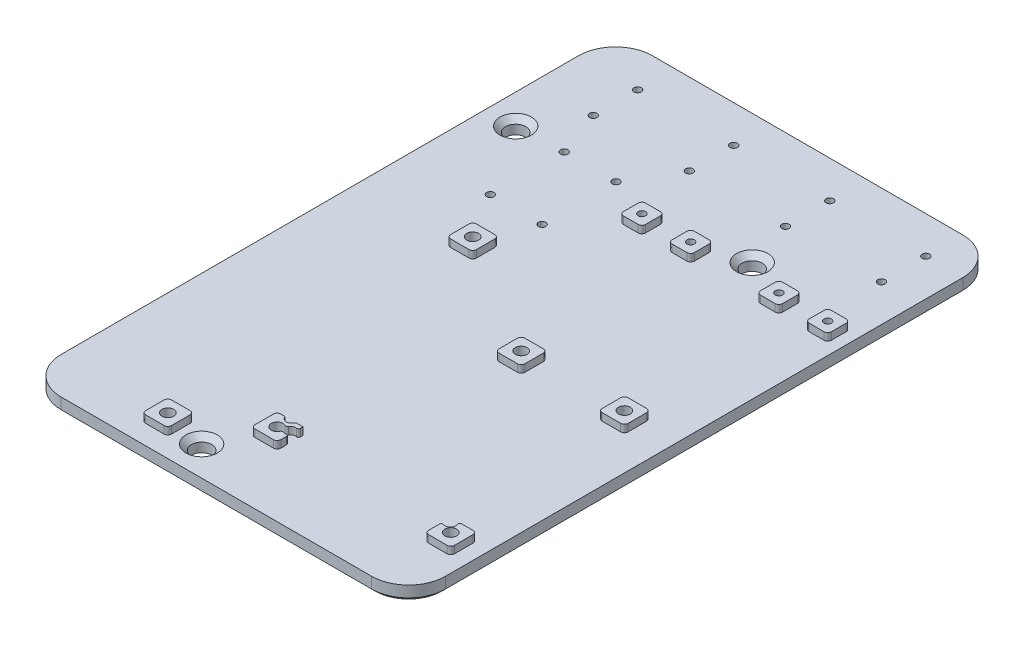
SolidWorks part; units mm, degrees
ref_plane "Front Plane" through (0, 0, 0) normal (0, 0, 1) x (1, 0, 0)
ref_plane "Top Plane" through (0, 0, 0) normal (0, 1, 0) x (1, 0, 0)
ref_plane "Right Plane" through (0, 0, 0) normal (1, 0, 0) x (0, 0, -1)
sketch "Sketch1" plane through (0, 0, 0) normal (0, 1, 0) x (1, 0, 0)
  line L1 (5, -5) -> (-99, -5)
  line L2 (5, -5) -> (5, 155)
  line L3 (5, 155) -> (-99, 155)
  line L4 (-99, -5) -> (-99, 155)
  circle A0 centre (-1.09, 114.53) radius 1
  circle A1 centre (-14.29, 114.53) radius 1
  circle A3 centre (-38.19, 114.53) radius 1
  circle A4 centre (-51.39, 114.53) radius 1
  circle A5 centre (-68.89, 86.25) radius 1.6
  circle A6 centre (-68.89, 3.75) radius 1.6
  circle A7 centre (-50.8, 15.24) radius 1.6
  circle A8 centre (-2.54, 13.97) radius 1.6
  circle A9 centre (-7.62, 66.04) radius 1.6
  circle A10 centre (-35.56, 66.04) radius 1.6
  point P35 (5, -2.4567)
  dimension "D3" = 2
  dimension "D4" = 160
  dimension "D5" = 3.2
  dimension "D1" = 104
  dimension "D2" = 5
  dimension "D6" = 5
extrude "Boss-Extrude1" add sketch "Sketch1" against normal blind 4
sketch "Sketch2" plane through (0, 0, 0) normal (0, -1, 0) x (-1, 0, 0)
  line L1 (65.39, 7.25) -> (72.39, 7.25)
  line L2 (65.39, 7.25) -> (65.39, 0.25)
  line L3 (65.39, 0.25) -> (72.39, 0.25)
  line L4 (72.39, 7.25) -> (72.39, 0.25)
  line L5 (65.39, 7.25) -> (72.39, 0.25) construction
  line L6 (65.39, 0.25) -> (72.39, 7.25) construction
  line L7 (65.39, 89.75) -> (72.39, 89.75)
  line L8 (65.39, 89.75) -> (65.39, 82.75)
  line L9 (65.39, 82.75) -> (72.39, 82.75)
  line L10 (72.39, 89.75) -> (72.39, 82.75)
  line L11 (65.39, 89.75) -> (72.39, 82.75) construction
  line L12 (65.39, 82.75) -> (72.39, 89.75) construction
  line L13 (48.39, 117.53) -> (54.39, 117.53)
  line L14 (48.39, 117.53) -> (48.39, 111.53)
  line L15 (48.39, 111.53) -> (54.39, 111.53)
  line L16 (54.39, 117.53) -> (54.39, 111.53)
  line L17 (48.39, 117.53) -> (54.39, 111.53) construction
  line L18 (48.39, 111.53) -> (54.39, 117.53) construction
  line L19 (41.19, 117.53) -> (35.19, 117.53)
  line L20 (41.19, 117.53) -> (41.19, 111.53)
  line L21 (41.19, 111.53) -> (35.19, 111.53)
  line L22 (35.19, 117.53) -> (35.19, 111.53)
  line L23 (41.19, 117.53) -> (35.19, 111.53) construction
  line L24 (41.19, 111.53) -> (35.19, 117.53) construction
  line L25 (11.29, 117.53) -> (17.29, 117.53)
  line L26 (11.29, 117.53) -> (11.29, 111.53)
  line L27 (11.29, 111.53) -> (17.29, 111.53)
  line L28 (17.29, 117.53) -> (17.29, 111.53)
  line L29 (11.29, 117.53) -> (17.29, 111.53) construction
  line L30 (11.29, 111.53) -> (17.29, 117.53) construction
  line L31 (4.09, 117.53) -> (-1.91, 117.53)
  line L32 (4.09, 117.53) -> (4.09, 111.53)
  line L33 (4.09, 111.53) -> (-1.91, 111.53)
  line L34 (-1.91, 117.53) -> (-1.91, 111.53)
  line L35 (4.09, 117.53) -> (-1.91, 111.53) construction
  line L36 (4.09, 111.53) -> (-1.91, 117.53) construction
  line L37 (-0.96, 17.47) -> (6.04, 17.47)
  line L38 (-0.96, 17.47) -> (-0.96, 10.47)
  line L39 (-0.96, 10.47) -> (6.04, 10.47)
  line L40 (6.04, 17.47) -> (6.04, 10.47)
  line L41 (-0.96, 17.47) -> (6.04, 10.47) construction
  line L42 (-0.96, 10.47) -> (6.04, 17.47) construction
  line L43 (54.3, 18.74) -> (47.3, 18.74)
  line L44 (54.3, 18.74) -> (54.3, 11.74)
  line L45 (54.3, 11.74) -> (47.3, 11.74)
  line L46 (47.3, 18.74) -> (47.3, 11.74)
  line L47 (54.3, 18.74) -> (47.3, 11.74) construction
  line L48 (54.3, 11.74) -> (47.3, 18.74) construction
  line L49 (32.06, 69.54) -> (39.06, 69.54)
  line L50 (32.06, 69.54) -> (32.06, 62.54)
  line L51 (32.06, 62.54) -> (39.06, 62.54)
  line L52 (39.06, 69.54) -> (39.06, 62.54)
  line L53 (32.06, 69.54) -> (39.06, 62.54) construction
  line L54 (32.06, 62.54) -> (39.06, 69.54) construction
  line L55 (4.12, 69.54) -> (11.12, 69.54)
  line L56 (4.12, 69.54) -> (4.12, 62.54)
  line L57 (4.12, 62.54) -> (11.12, 62.54)
  line L58 (11.12, 69.54) -> (11.12, 62.54)
  line L59 (4.12, 69.54) -> (11.12, 62.54) construction
  line L60 (4.12, 62.54) -> (11.12, 69.54) construction
  circle A1 centre (35.56, 66.04) radius 1.6
  circle A2 centre (35.56, 66.04) radius 1.6
  circle A3 centre (68.89, 86.25) radius 1.6
  circle A4 centre (68.89, 86.25) radius 1.6
  circle A5 centre (51.39, 114.53) radius 1
  circle A6 centre (51.39, 114.53) radius 1
  circle A7 centre (38.19, 114.53) radius 1
  circle A8 centre (38.19, 114.53) radius 1
  circle A9 centre (14.29, 114.53) radius 1
  circle A10 centre (14.29, 114.53) radius 1
  circle A11 centre (1.09, 114.53) radius 1
  circle A12 centre (1.09, 114.53) radius 1
  circle A13 centre (7.62, 66.04) radius 1.6
  circle A14 centre (7.62, 66.04) radius 1.6
  circle A15 centre (2.54, 13.97) radius 1.6
  circle A16 centre (2.54, 13.97) radius 1.6
  circle A17 centre (50.8, 15.24) radius 1.6
  circle A18 centre (50.8, 15.24) radius 1.6
  circle A19 centre (68.89, 3.75) radius 1.6
  circle A20 centre (68.89, 3.75) radius 1.6
  point P0 (68.89, 3.75)
  point P6 (68.89, 86.25)
  point P12 (51.39, 114.53)
  point P18 (38.19, 114.53)
  point P24 (14.29, 114.53)
  point P30 (1.09, 114.53)
  point P36 (2.54, 13.97)
  point P42 (50.8, 15.24)
  point P48 (35.56, 66.04)
  point P54 (7.62, 66.04)
  dimension "D1" = 6
  dimension "D2" = 7
  dimension "D3" = 0
  dimension "D4" = 0
  dimension "D5" = 0
  dimension "D6" = 0
  dimension "D7" = 0
  dimension "D8" = 0
  dimension "D9" = 0
  dimension "D10" = 0
  dimension "D11" = 0
  dimension "D12" = 0
extrude "Boss-Extrude2" add sketch "Sketch2" against normal blind 2
sketch "Sketch3" plane through (0, 2, 0) normal (0, 1, 0) x (1, 0, 0)
  line L0 (-47.3, 18.74) -> (-47.3, 11.74) construction
  line L1 (-54.3, 18.74) -> (-47.3, 18.74) construction
  line L2 (-4.8463, 16.1519) -> (-6.8463, 18.1519) construction
  line L3 (-5.8363, 15.162) -> (-7.8363, 17.162)
  line L4 (-3.8564, 17.1419) -> (-5.8564, 19.1419)
  line L5 (-6.04, 17.47) -> (0.96, 17.47) construction
  circle A0 centre (-50.7183, 19.0424) radius 1.4
  circle A1 centre (-48.1702, 16.1519) radius 1.4
  circle A2 centre (-4.8463, 16.1519) radius 1.4 construction
  arc A3 (-5.8363, 15.162) -> (-3.8564, 17.1419) centre (-4.8463, 16.1519) ccw
  arc A4 (-5.8564, 19.1419) -> (-7.8363, 17.162) centre (-6.8463, 18.1519) ccw
  point P7 (-5.8463, 17.1519)
  point P16 (0, 0)
  point P17 (0, 0)
  dimension "D1" = 135
  dimension "D2" = 2.8
  dimension "D3" = 2
  dimension "D4" = 42.4537
  dimension "D5" = 0.8702
  dimension "D6" = 3.4183
  dimension "D7" = 0.3024
  dimension "D8" = 2.5881
extrude "Cut-Extrude1" cut sketch "Sketch3" against normal blind 2
fillet "Fillet1" radius 0.5 8 edges at (-52.0853, 1, -18.74) (-49.3514, 1, -18.74) (-47.3, 1, -17.2486) (-47.3, 1, -15.0552) (-49.5661, 1, -16.2586) (-49.2004, 1, -15.204) (-6.04, 1, -15.3657) (-4.1845, 1, -17.47)
fillet "Fillet2" radius 1 38 edges at (1.91, 1, -117.53) (-17.29, 1, -117.53) (-11.29, 1, -117.53) (-4.12, 1, -69.54) (-4.12, 1, -62.54) (-11.12, 1, -62.54) (-11.12, 1, -69.54) (-4.09, 1, -111.53) (1.91, 1, -111.53) (-4.09, 1, -117.53) (-11.29, 1, -111.53) (-17.29, 1, -111.53) (-32.06, 1, -62.54) (-35.19, 1, -111.53) (-48.39, 1, -117.53) (-48.39, 1, -111.53) (-54.39, 1, -111.53) (-65.39, 1, -82.75) (-72.39, 1, -82.75) (-65.39, 1, -89.75) (-72.39, 1, -89.75) (-39.06, 1, -62.54) (-39.06, 1, -69.54) (-32.06, 1, -69.54) (-41.19, 1, -111.53) (-35.19, 1, -117.53) (-41.19, 1, -117.53) (-54.39, 1, -117.53) (-65.39, 1, -7.25) (-72.39, 1, -7.25) (-72.39, 1, -0.25) (-65.39, 1, -0.25) (0.96, 1, -17.47) (0.96, 1, -10.47) (-6.04, 1, -10.47) (-54.3, 1, -11.74) (-47.3, 1, -11.74) (-54.3, 1, -18.74)
sketch "Sketch4" plane through (0, -4, 0) normal (0, -1, 0) x (1, 0, 0)
  line L1 (-32.3268, -66.04) -> (-33.9434, -63.24)
  line L2 (-33.9434, -63.24) -> (-37.1766, -63.24)
  line L3 (-37.1766, -63.24) -> (-38.7932, -66.04)
  line L4 (-38.7932, -66.04) -> (-37.1766, -68.84)
  line L5 (-37.1766, -68.84) -> (-33.9434, -68.84)
  line L6 (-33.9434, -68.84) -> (-32.3268, -66.04)
  line L7 (-4.3868, -66.04) -> (-6.0034, -63.24)
  line L8 (-6.0034, -63.24) -> (-9.2366, -63.24)
  line L9 (-9.2366, -63.24) -> (-10.8532, -66.04)
  line L10 (-10.8532, -66.04) -> (-9.2366, -68.84)
  line L11 (-9.2366, -68.84) -> (-6.0034, -68.84)
  line L12 (-6.0034, -68.84) -> (-4.3868, -66.04)
  line L13 (-65.6568, -86.25) -> (-67.2734, -83.45)
  line L14 (-67.2734, -83.45) -> (-70.5066, -83.45)
  line L15 (-70.5066, -83.45) -> (-72.1232, -86.25)
  line L16 (-72.1232, -86.25) -> (-70.5066, -89.05)
  line L17 (-70.5066, -89.05) -> (-67.2734, -89.05)
  line L18 (-67.2734, -89.05) -> (-65.6568, -86.25)
  line L19 (0.6932, -13.97) -> (-0.9234, -11.17)
  line L20 (-0.9234, -11.17) -> (-4.1566, -11.17)
  line L21 (-4.1566, -11.17) -> (-5.7732, -13.97)
  line L22 (-5.7732, -13.97) -> (-4.1566, -16.77)
  line L23 (-4.1566, -16.77) -> (-0.9234, -16.77)
  line L24 (-0.9234, -16.77) -> (0.6932, -13.97)
  line L25 (-47.5668, -15.24) -> (-49.1834, -12.44)
  line L26 (-49.1834, -12.44) -> (-52.4166, -12.44)
  line L27 (-52.4166, -12.44) -> (-54.0332, -15.24)
  line L28 (-54.0332, -15.24) -> (-52.4166, -18.04)
  line L29 (-52.4166, -18.04) -> (-49.1834, -18.04)
  line L30 (-49.1834, -18.04) -> (-47.5668, -15.24)
  line L31 (-65.6568, -3.75) -> (-67.2734, -0.95)
  line L32 (-67.2734, -0.95) -> (-70.5066, -0.95)
  line L33 (-70.5066, -0.95) -> (-72.1232, -3.75)
  line L34 (-72.1232, -3.75) -> (-70.5066, -6.55)
  line L35 (-70.5066, -6.55) -> (-67.2734, -6.55)
  line L36 (-67.2734, -6.55) -> (-65.6568, -3.75)
  circle A0 centre (-35.56, -66.04) radius 2.8 construction
  circle A1 centre (-7.62, -66.04) radius 2.8 construction
  circle A2 centre (-68.89, -86.25) radius 2.8 construction
  circle A3 centre (-2.54, -13.97) radius 2.8 construction
  circle A4 centre (-50.8, -15.24) radius 2.8 construction
  circle A5 centre (-68.89, -3.75) radius 2.8 construction
  point P46 (0, 0)
  dimension "D1" = 5.6
  dimension "D2" = 5.6
  dimension "D3" = 5.6
  dimension "D4" = 5.6
  dimension "D5" = 5.6
  dimension "D6" = 5.6
extrude "Cut-Extrude2" cut sketch "Sketch4" against normal blind 2.4
sketch "Sketch5" plane through (0, 0, 0) normal (0, 1, 0) x (1, 0, 0)
  line L0 (-99, -5) -> (5, -5) construction
  line L1 (-99, 155) -> (-99, -5) construction
  line L2 (5, 155) -> (-99, 155) construction
  circle A0 centre (-59, 3) radius 2.75
  circle A1 centre (-91, 120) radius 2.75
  circle A2 centre (-27, 120) radius 2.75
  point P12 (0, 0)
  dimension "D1" = 5.5
  dimension "D2" = 8
  dimension "D3" = 40
  dimension "D4" = 8
  dimension "D5" = 72
  dimension "D6" = 35
extrude "Cut-Extrude3" cut sketch "Sketch5" against normal through all
chamfer "Chamfer1" distance 1.5 angle 45 3 edges at (-91, 0, -117.25) (-59, 0, -0.25) (-27, 0, -117.25)
fillet "Fillet3" radius 10 4 edges at (-99, -2, -155) (5, -2, -155) (-99, -2, 5) (5, -2, 5)
sketch "Sketch6" plane through (0, 0, 0) normal (0, 1, 0) x (1, 0, 0)
  circle A0 centre (-5, 145) radius 1
  arc A1 (5, 145) -> (-5, 155) centre (-5, 145) ccw construction
  point P2 (0, 0)
  dimension "D1" = 2
extrude "Cut-Extrude4" cut sketch "Sketch6" against normal through all
pattern_linear "LPattern1" count 4 spacing 26 along (-1, 0, 0) count 2 spacing 12 along (0, 0, 1) of "Cut-Extrude4"
sketch "Sketch7" plane through (0, 0, 0) normal (0, 1, 0) x (1, 0, 0)
  line L0 (-54.39, 112.53) -> (-54.39, 116.53) construction
  line L1 (-53.39, 117.53) -> (-49.39, 117.53) construction
  circle A0 centre (-78.39, 120.53) radius 1
  circle A1 centre (-64.39, 120.53) radius 1
  circle A2 centre (-78.39, 100.53) radius 1
  circle A3 centre (-64.39, 100.53) radius 1
  point P8 (0, 0)
  point P9 (0, 0)
  point P10 (0, 0)
  point P15 (-58.6388, 100.53)
  dimension "D3" = 2
  dimension "D4" = 10
  dimension "D1" = 14
  dimension "D2" = 20
  dimension "D5" = 3
extrude "Cut-Extrude5" cut sketch "Sketch7" against normal through all
chamfer "Chamfer2" distance 1 angle 45 8 edges at (-47, -4, -155) (-96.0711, -4, -152.0711) (2.0711, -4, -152.0711) (-99, -4, -75) (5, -4, -75) (-96.0711, -4, 2.0711) (2.0711, -4, 2.0711) (-47, -4, 5)
